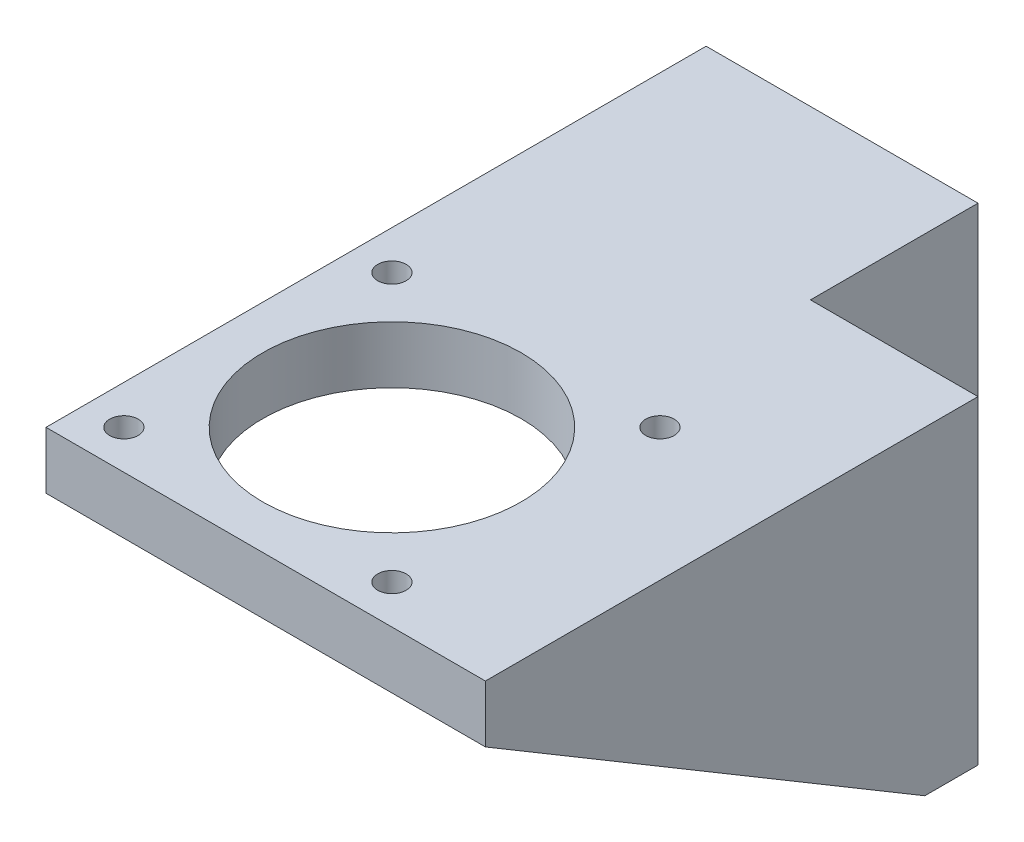
SolidWorks part; units mm, degrees
ref_plane "Front Plane" through (0, 0, 0) normal (0, 0, 1) x (1, 0, 0)
ref_plane "Top Plane" through (0, 0, 0) normal (0, 1, 0) x (1, 0, 0)
ref_plane "Right Plane" through (0, 0, 0) normal (1, 0, 0) x (0, 0, -1)
sketch "Sketch1" plane through (0, 0, 0) normal (0, 1, 0) x (1, 0, 0)
  line L1 (0, 0) -> (20, 0)
  line L2 (0, 0) -> (0, -6.35)
  line L3 (0, -6.35) -> (20, -6.35)
  line L4 (20, 0) -> (20, -6.35)
  line L5 (0, 0) -> (-6.35, 0)
  line L6 (0, 0) -> (0, 20)
  line L7 (0, 20) -> (-6.35, 20)
  line L8 (-6.35, 0) -> (-6.35, 20)
  line L9 (-6.35, 0) -> (0, 0)
  line L10 (-6.35, 0) -> (-6.35, -6.35)
  line L11 (-6.35, -6.35) -> (0, -6.35)
  line L12 (0, 0) -> (0, -6.35)
  dimension "D2" = 6.35
  dimension "D3" = 20
  dimension "D4" = 20
extrude "Boss-Extrude1" add sketch "Sketch1" along normal blind 38.1 contours L4 L1 L2 L3 | L10 L11 L2 L5 | L8 L5 L6 L7
sketch "Sketch2" plane through (0, 38.1, 0) normal (0, 1, 0) x (1, 0, 0)
  line L0 (-32.46, -147.5842) -> (-6.35, -147.5842)
  line L1 (20, -6.35) -> (-32.46, -6.35)
  line L2 (20, -6.35) -> (20, -58.81)
  line L3 (20, -58.81) -> (-32.46, -58.81)
  line L4 (-32.46, -6.35) -> (-32.46, -58.81)
  line L5 (-6.35, 20) -> (-32.46, 20)
  line L6 (-6.35, 20) -> (-6.35, -6.35)
  line L7 (-6.35, -6.35) -> (-32.46, -6.35)
  line L8 (-32.46, 20) -> (-32.46, -6.35)
  line L9 (20, -121.2342) -> (20, -68.7742)
  line L10 (8.84, -58.81) -> (-32.46, -17.51)
  line L11 (-32.46, -58.81) -> (8.84, -58.81)
  line L12 (-32.46, -58.81) -> (-32.46, -17.51)
  line L13 (-32.46, -17.51) -> (8.84, -17.51)
  line L14 (8.84, -58.81) -> (8.84, -17.51)
  line L15 (8.84, -17.51) -> (-32.46, -58.81)
  line L16 (4.19, -105.4242) -> (4.19, -74.4242)
  line L18 (-27.81, -54.16) -> (4.19, -54.16)
  line L19 (-27.81, -54.16) -> (-27.81, -22.16)
  line L20 (-27.81, -22.16) -> (4.19, -22.16)
  line L21 (4.19, -54.16) -> (4.19, -22.16)
  line L22 (-27.81, -54.16) -> (4.19, -22.16) construction
  line L23 (-27.81, -22.16) -> (4.19, -54.16) construction
  circle A0 centre (-11.81, -38.16) radius 15.432
  circle A1 centre (4.19, -74.4242) radius 1.7
  circle A2 centre (4.19, -54.16) radius 1.7
  circle A3 centre (4.19, -22.16) radius 1.7
  circle A4 centre (-27.81, -22.16) radius 1.7
  circle A5 centre (-27.81, -54.16) radius 1.7
  circle A6 centre (4.19, -74.4242) radius 1.7 construction
  circle A8 centre (-11.3143, -89.9922) radius 15.432
  circle A9 centre (-11.3143, -89.9922) radius 15.432 construction
  line M24 (-6.35, 20) -> (-6.35, -6.35)
  line M25 (-6.35, -6.35) -> (20, -6.35)
  dimension "D3" = 0
  dimension "D4" = 0
  dimension "D1" = 41.3
  dimension "D2" = 41.3
extrude "Boss-Extrude2" add sketch "Sketch2" against normal up to surface (6.819 mm away) contours A5 L15 L3 L10 A2 L18 | A3 L21 A2 L10 L14 L15 | L14 L3 L2 L1 L4 L13 M25 | L5 L8 L1 M24 | A4 L20 A3 L15 L13 L10 | A5 L19 A4 L10 L4 L15 | A5 L15 A0 L10 A4 L19 | A4 L10 A0 L15 A3 L20 | A3 L15 A0 L10 A2 L21 | A5 L18 A2 L10 A0 L15
sketch "Sketch3" plane through (20, 0, 0) normal (1, 0, 0) x (0, 0, -1)
  line L0 (-58.81, 31.281) -> (-6.35, 0)
  line L1 (-6.35, 0) -> (-6.35, 31.281)
  line L2 (-6.35, 31.281) -> (-58.81, 31.281)
extrude "Boss-Extrude3" add sketch "Sketch3" against normal blind 2.54
sketch "Sketch4" plane through (0, 0, -20) normal (0, 0, -1) x (-1, 0, 0)
  line L0 (6.35, 0) -> (32.46, 31.281)
  line L1 (32.46, 31.281) -> (6.35, 31.281)
  line L2 (6.35, 31.281) -> (6.35, 0)
extrude "Boss-Extrude4" add sketch "Sketch4" against normal blind 2.54
sketch "Sketch5" plane through (0, 0, 6.35) normal (0, 0, 1) x (1, 0, 0)
  line L0 (-6.35, -0.469) -> (-32.46, 31.281)
  line L1 (-6.35, -0.469) -> (-6.35, 31.281)
  line L2 (-6.35, 31.281) -> (-32.46, 31.281)
extrude "Boss-Extrude5" add sketch "Sketch5" against normal blind 2.54
sketch "Sketch6" plane through (-6.35, 0, 0) normal (-1, 0, 0) x (0, 0, 1)
  line L0 (3.81, 31.281) -> (-17.46, 31.281) construction
  line L1 (-20, 0) -> (0, 0)
  line L2 (-20, 0) -> (-20, 31.281)
  line L3 (-20, 31.281) -> (0, 31.281)
  line L4 (0, 0) -> (0, 31.281)
  line L5 (0, 15.6405) -> (-20, 15.6405)
  line L6 (-10, 15.6405) -> (-10, 0)
  line L7 (-10, 15.6405) -> (-10, 31.281)
  point P11 (-10, 23.4608)
  point P13 (-10, 7.8203)
  dimension "D1" = 20
hole_wizard "M4 Clearance Hole1" positions "Sketch7" profile "Sketch8" hole size "M4" standard "ANSI Metric" end condition through all
sketch "Sketch7" plane through (-6.35, 0, 0) normal (-1, 0, 0) x (0, 0, 1)
  point P0 (-10, 23.4608)
  point P3 (-10, 7.8203)
sketch "Sketch8" plane through (-6.35, 23.4608, -10) normal (0, 1, 0) x (0, 0, 1)
  line L0 (0, 0) -> (0, 26.35)
  line L1 (0, 26.35) -> (2.25, 26.35)
  line L2 (2.25, 26.35) -> (2.25, 0)
  line L5 (2.25, 0) -> (0, 0)
  line L11 (0, -6.35) -> (0, 107.95) construction
  dimension "Thru Hole Dia." = 4.5
  dimension "Thru Hole Depth" = 26.35
sketch "Sketch9" plane through (0, 0, 6.35) normal (0, 0, 1) x (1, 0, 0)
  line L0 (17.46, 31.281) -> (-32.46, 31.281) construction
  line L1 (20, 0) -> (0, 0)
  line L2 (20, 0) -> (20, 31.281)
  line L3 (20, 31.281) -> (0, 31.281)
  line L4 (0, 0) -> (0, 31.281)
  line L5 (0, 15.6405) -> (20, 15.6405)
  line L6 (10, 15.6405) -> (10, 0)
  line L7 (10, 15.6405) -> (10, 31.281)
  point P11 (10, 23.4608)
  point P13 (10, 7.8203)
  dimension "D1" = 20
hole_wizard "M4 Clearance Hole2" positions "Sketch10" profile "Sketch11" hole size "M4" standard "ANSI Metric" end condition through all
sketch "Sketch10" plane through (0, 0, 6.35) normal (0, 0, 1) x (1, 0, 0)
  point P0 (10, 7.8203)
  point P3 (10, 23.4608)
sketch "Sketch11" plane through (10, 7.8203, 6.35) normal (1, 0, 0) x (0, -1, 0)
  line L0 (0, 0) -> (0, 26.35)
  line L1 (0, 26.35) -> (2.25, 26.35)
  line L2 (2.25, 26.35) -> (2.25, 0)
  line L5 (2.25, 0) -> (0, 0)
  line L11 (0, -6.35) -> (0, 107.95) construction
  dimension "Thru Hole Dia." = 4.5
  dimension "Thru Hole Depth" = 26.35
